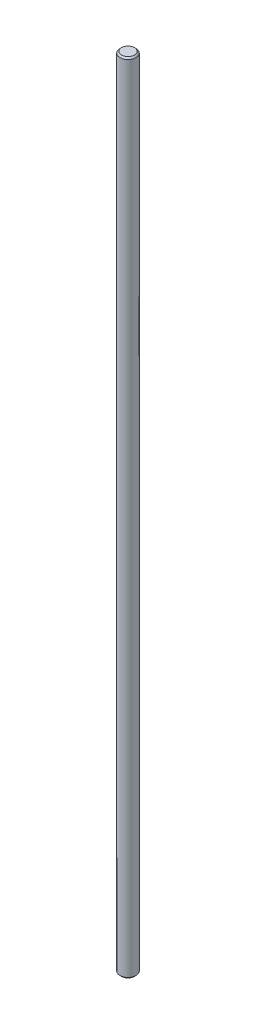
SolidWorks part; units mm, degrees
ref_plane "Front Plane" through (0, 0, 0) normal (0, 0, 1) x (1, 0, 0)
ref_plane "Top Plane" through (0, 0, 0) normal (0, 1, 0) x (1, 0, 0)
ref_plane "Right Plane" through (0, 0, 0) normal (1, 0, 0) x (0, 0, -1)
sketch "Sketch1" plane through (0, 0, 0) normal (0, 1, 0) x (1, 0, 0)
  circle A0 centre (0, 0) radius 4
  dimension "D1" = 8
extrude "Boss-Extrude1" add sketch "Sketch1" along normal blind 400
chamfer "Chamfer1" distance 0.75 angle 45 2 edges at (0, 0, 4) (0, 400, 4)
